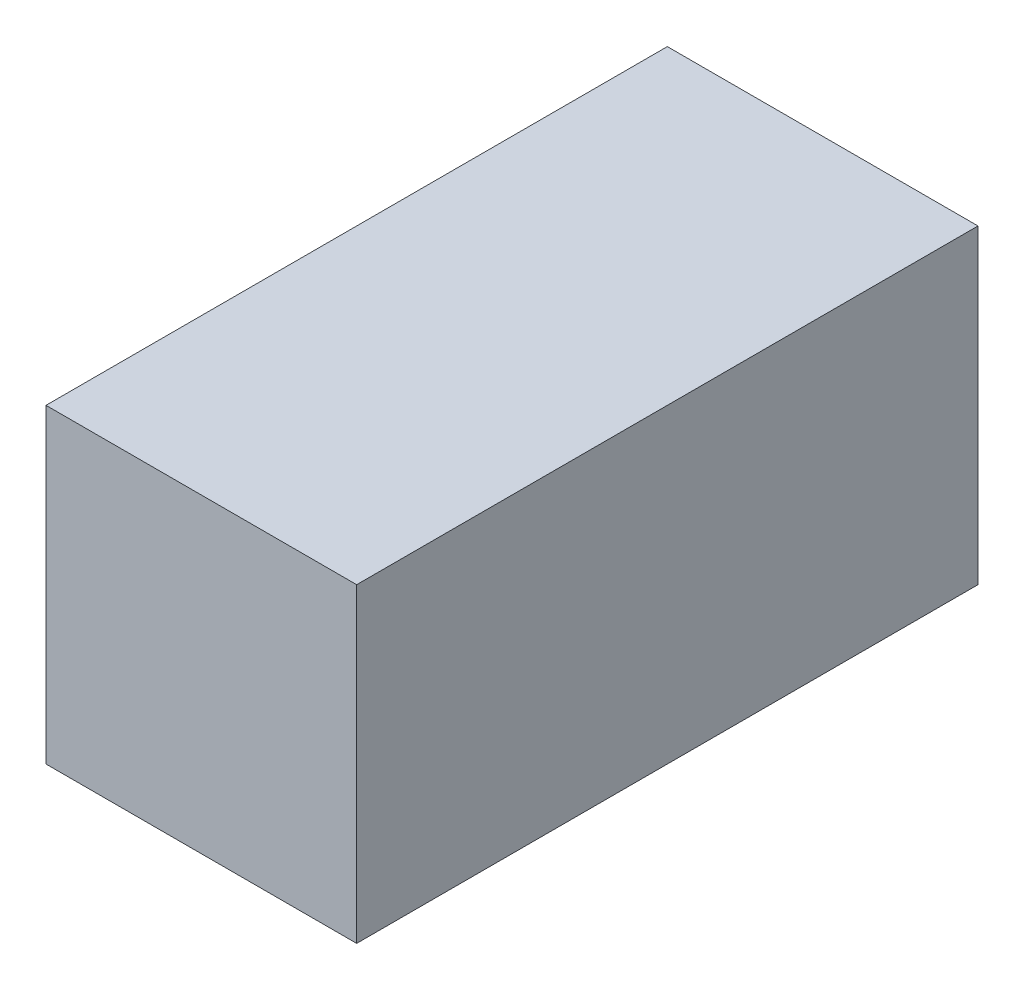
SolidWorks part; units mm, degrees
ref_plane "Front Plane" through (0, 0, 0) normal (0, 0, 1) x (1, 0, 0)
ref_plane "Top Plane" through (0, 0, 0) normal (0, 1, 0) x (1, 0, 0)
ref_plane "Right Plane" through (0, 0, 0) normal (1, 0, 0) x (0, 0, -1)
sketch "Sketch1" plane through (0, 0, 0) normal (0, 0, 1) x (1, 0, 0)
  line L0 (0, 0) -> (50, 0)
  line L1 (50, 0) -> (50, 50)
  line L2 (50, 50) -> (0, 50)
  line L3 (0, 50) -> (0, 0)
  dimension "D1" = 50
  dimension "D2" = 50
extrude "Boss-Extrude1" add sketch "Sketch1" along normal blind 100
